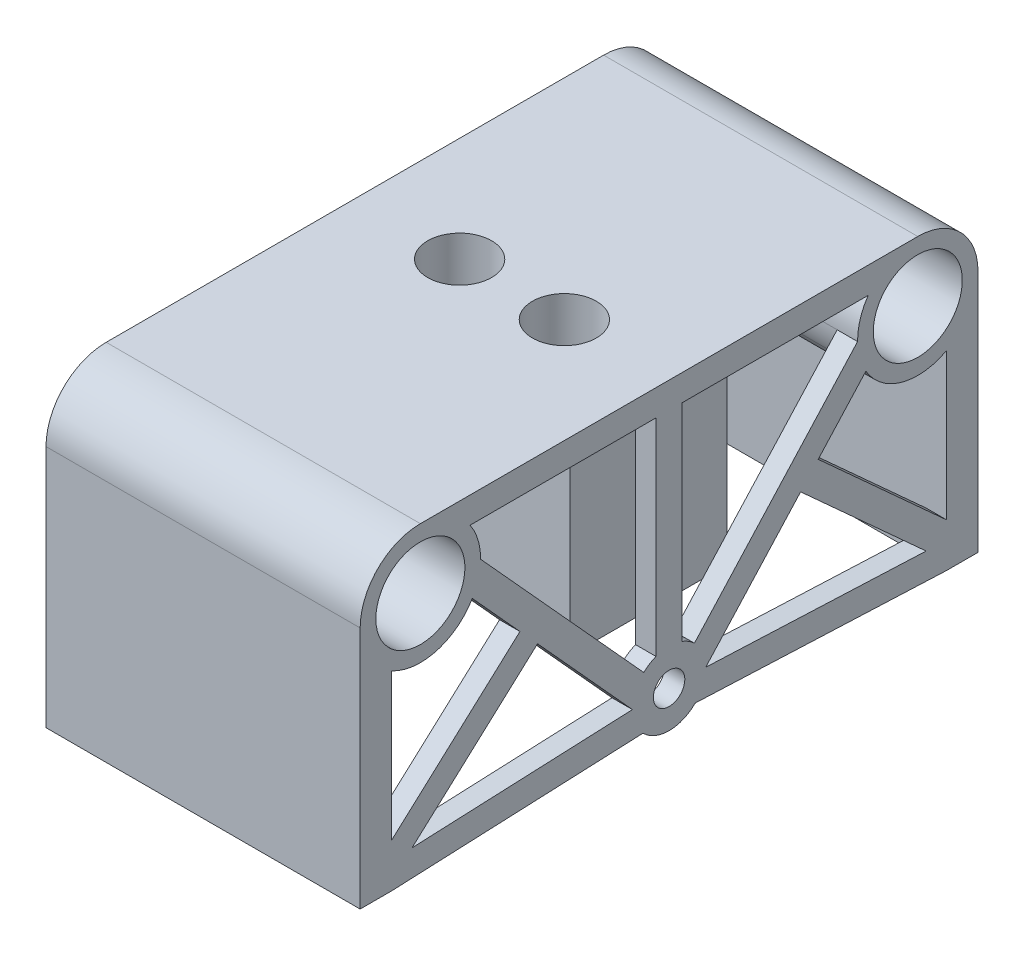
SolidWorks part; units mm, degrees
ref_plane "Front Plane" through (0, 0, 0) normal (0, 0, 1) x (1, 0, 0)
ref_plane "Top Plane" through (0, 0, 0) normal (0, 1, 0) x (1, 0, 0)
ref_plane "Right Plane" through (0, 0, 0) normal (1, 0, 0) x (0, 0, -1)
sketch "Sketch4" plane through (0, 0, 0) normal (0, 0, 1) x (1, 0, 0)
  line L0 (-30, 29) -> (-30, -29)
  line L1 (-30, -29) -> (30, -29)
  line L2 (30, -29) -> (30, 29)
  line L3 (30, 29) -> (-30, 29)
  point P4 (30, 0)
  point P5 (0, 29)
  dimension "D1" = 58
  dimension "D2" = 60
extrude "Boss-Extrude2" add sketch "Sketch4" along normal mid plane 118
sketch "Sketch5" plane through (30, 0, 0) normal (1, 0, 0) x (0, 0, -1)
  line L0 (-7.1278, -22) -> (-53.0521, -25.7381) construction
  line L1 (-53.0521, -30.7546) -> (-5.035, -26.8462) construction
  line L2 (-39.0141, 14.8656) -> (-7.1278, -22) construction
  line L3 (-53.0521, -30.7546) -> (-53.0521, 7.429) construction
  line L6 (-36.121, 19.1639) -> (-4.8602, -16.9785)
  line L8 (-38.0132, 24) -> (-2.4867, 24)
  line L10 (0, -22) -> (0, 29) construction
  line L11 (-2.4867, 24) -> (-2.4867, -15.4691)
  line L29 (0, 0) -> (0, 42.8689) construction
  line L30 (-59, 29) -> (59, 29) construction
  line L31 (-59, -29) -> (-59, 29) construction
  line L32 (-48.8335, -25.3947) -> (-23.2963, -3.3067) construction
  line L33 (-26.5672, 0.475) -> (-53.0521, -22.4327)
  line L34 (-43.6385, -14.2906) -> (-40.3676, -18.0723) construction
  line L35 (-42.0031, -16.1814) -> (-53.0521, -25.7381) construction
  line L36 (-26.5672, 0.475) -> (-37.0815, 12.6313)
  line L37 (-53.0521, 7.429) -> (-53.0521, -22.4327)
  line L38 (-23.2963, -3.3067) -> (-48.8335, -25.3947)
  line L39 (-48.8335, -25.3947) -> (-7.1278, -22)
  line L40 (-7.1278, -22) -> (-23.2963, -3.3067)
  line L41 (-5.035, -26.8462) -> (-53.0521, -30.7546)
  line L42 (-53.0521, -30.7546) -> (53.0521, -30.7546)
  line L43 (5.035, -26.8462) -> (53.0521, -30.7546)
  line L44 (38.0132, 24) -> (2.4867, 24)
  line L45 (2.4867, 24) -> (2.4867, -15.4691)
  line L46 (36.121, 19.1639) -> (4.8602, -16.9785)
  line L47 (48.8335, -25.3947) -> (7.1278, -22)
  line L48 (23.2963, -3.3067) -> (48.8335, -25.3947)
  line L49 (7.1278, -22) -> (23.2963, -3.3067)
  line L50 (26.5672, 0.475) -> (37.0815, 12.6313)
  line L51 (26.5672, 0.475) -> (53.0521, -22.4327)
  line L52 (53.0521, 7.429) -> (53.0521, -22.4327)
  line L53 (-47.5, 17.5) -> (0, 17.5) construction
  line L54 (0, 17.5) -> (0, -22) construction
  circle A8 centre (-47.5, 17.5) radius 8.5
  circle A9 centre (-47.5, 17.5) radius 11.5
  circle A10 centre (47.5, 17.5) radius 8.5
  circle A11 centre (47.5, 17.5) radius 11.5
  circle A12 centre (0, -22) radius 3
  arc A13 (-53.0521, 7.429) -> (-37.0815, 12.6313) centre (-47.5, 17.5) ccw
  arc A14 (-5.035, -26.8462) -> (5.035, -26.8462) centre (0, -22) ccw
  arc A15 (-38.0132, 24) -> (-36.121, 19.1639) centre (-47.5, 17.5) cw
  arc A16 (2.4867, -15.4691) -> (4.8602, -16.9785) centre (0, -22) cw
  arc A17 (-2.4867, -15.4691) -> (-4.8602, -16.9785) centre (0, -22) ccw
  arc A18 (38.0132, 24) -> (36.121, 19.1639) centre (47.5, 17.5) ccw
  arc A19 (53.0521, 7.429) -> (37.0815, 12.6313) centre (47.5, 17.5) cw
  point P3 (-47.5, 17.5)
  point P18 (0, -30.7546)
  point P27 (-42.0031, -16.1814)
  point P58 (59, 17.5)
  dimension "D1" = 17
  dimension "D4" = 6
  dimension "D3" = 5
  dimension "D5" = 39.5
  dimension "D6" = 5
  dimension "D7" = 5
  dimension "D2" = 3
sketch "Sketch6" plane through (-30, 0, 0) normal (-1, 0, 0) x (0, 0, 1)
  line L0 (0, -6.9366) -> (0, 49.2251) construction
  line L1 (0, -22) -> (0, 29) construction
  line L2 (-7, -22) -> (-53, -23.9953) construction
  line L3 (-53, -29) -> (-4.9821, -26.9172) construction
  line L4 (-39.7346, 14.0434) -> (-7, -22) construction
  line L5 (-53, -29) -> (-53, 7.4005) construction
  line L8 (-36.0007, 17.3692) -> (-4.8392, -16.9421)
  line L10 (-38.0132, 24) -> (-2.5, 24)
  line L12 (0, -22) -> (0, 29) construction
  line L13 (-2.5, 24) -> (-2.5, -15.4617)
  line L31 (-49.095, -23.8259) -> (-25.1183, -2.0503) construction
  line L32 (-28.4798, 1.651) -> (-53, -20.6182)
  line L33 (-43.8665, -12.3231) -> (-40.505, -16.0245) construction
  line L34 (-42.1857, -14.1738) -> (-53, -23.9953) construction
  line L35 (-28.4798, 1.651) -> (-37.5841, 11.6756)
  line L36 (-53, 7.4005) -> (-53, -20.6182)
  line L37 (-25.1183, -2.0503) -> (-49.095, -23.8259)
  line L38 (-49.095, -23.8259) -> (-7, -22)
  line L39 (-7, -22) -> (-25.1183, -2.0503)
  line L40 (-4.9821, -26.9172) -> (-53, -29)
  line L42 (4.9821, -26.9172) -> (53, -29)
  line L43 (38.0132, 24) -> (2.5, 24)
  line L44 (2.5, 24) -> (2.5, -15.4617)
  line L45 (36.0007, 17.3692) -> (4.8392, -16.9421)
  line L46 (49.095, -23.8259) -> (7, -22)
  line L47 (25.1182, -2.0503) -> (49.095, -23.8259)
  line L48 (7, -22) -> (25.1182, -2.0503)
  line L49 (28.4798, 1.651) -> (37.584, 11.6756)
  line L50 (28.4798, 1.651) -> (53, -20.6182)
  line L51 (53, 7.4005) -> (53, -20.6182)
  line L52 (-53, -29) -> (-53, -39.7033)
  line L53 (-53, -39.7033) -> (53, -37.9369)
  line L54 (53, -37.9369) -> (53, -29)
  line L55 (-47.5, 29) -> (-47.5, 35.7267)
  line L56 (-47.5, 35.7267) -> (-66.8543, 35.7267)
  line L57 (-66.8543, 35.7267) -> (-66.1473, 17.5)
  line L58 (-66.1473, 17.5) -> (-59, 17.5)
  line L59 (47.5, 29) -> (47.0761, 34.9367)
  line L60 (47.0761, 34.9367) -> (67.1714, 34.5747)
  line L61 (67.1714, 34.5747) -> (67.1714, 17.5)
  line L62 (67.1714, 17.5) -> (59, 17.5)
  circle A0 centre (-47.5, 17.5) radius 8.5
  arc A1 (-47.5, 29) -> (-59, 17.5) centre (-47.5, 17.5) ccw
  circle A10 centre (0, -22) radius 3
  arc A11 (-53, 7.4005) -> (-37.5841, 11.6756) centre (-47.5, 17.5) ccw
  arc A12 (-4.9821, -26.9172) -> (4.9821, -26.9172) centre (0, -22) ccw
  arc A13 (-38.0132, 24) -> (-36.0007, 17.3692) centre (-47.5, 17.5) cw
  arc A14 (2.5, -15.4617) -> (4.8392, -16.9421) centre (0, -22) cw
  arc A15 (-2.5, -15.4617) -> (-4.8392, -16.9421) centre (0, -22) ccw
  arc A16 (38.0132, 24) -> (36.0007, 17.3692) centre (47.5, 17.5) ccw
  arc A17 (53, 7.4005) -> (37.584, 11.6756) centre (47.5, 17.5) cw
  circle A18 centre (47.5, 17.5) radius 8.5
  circle A19 centre (-47.5, 17.5) radius 11.5 construction
  arc A20 (-53, 7.4005) -> (-38.0132, 24) centre (-47.5, 17.5) ccw
  arc A21 (37.0273, 22.251) -> (38.0132, 24) centre (47.5, 17.5) cw
  arc A22 (47.5, 29) -> (59, 17.5) centre (47.5, 17.5) cw
  arc A23 (53, 7.4005) -> (51.5815, 6.7487) centre (47.5, 17.5) cw
  point P13 (-47.5, 17.5)
  point P28 (0, -29)
  point P37 (-42.1857, -14.1738)
  line M23 (-59, 29) -> (-59, -29)
  line M24 (-59, -29) -> (59, -29)
  line M25 (59, -29) -> (59, 29)
  line M26 (59, 29) -> (-59, 29)
  dimension "D2" = 17
  dimension "D1" = 3
extrude "Cut-Extrude2" cut sketch "Sketch6" against normal through all contours L57 L58 L55 L56 M23 M26 | A1 M26 M23 | A0 | A15 L13 L10 A13 L8 | A20 L36 L32 L35 | L38 L39 L37 | A12 L40 M24 | A12 L42 M24 | A10 | A16 L43 L44 A14 L45 | L48 L46 L47 | L51 A17 L49 L50 | A18 | L62 L61 L60 L59 M26 M25 | A22 M26 M25
sketch "Sketch7" plane through (-30, 0, 0) normal (-1, 0, 0) x (0, 0, 1)
  line L9 (-15, 24) -> (-15, -11)
  line L10 (-38.0132, 24) -> (-2.5, 24) construction
  line L11 (-15, -11) -> (15.389, -11)
  line L12 (15.389, -11) -> (15, 24)
  line L14 (15, 24) -> (-15, 24)
  line L15 (47.5, 29) -> (-47.5, 29) construction
  point P5 (0, 24)
  dimension "D1" = 30
  dimension "D2" = 40
extrude "Boss-Extrude3" add sketch "Sketch7" along normal mid plane 52.2 from surface at -30 starting at plane "Right Plane"
sketch "Sketch8" plane through (-26.1, 0, 0) normal (-1, 0, 0) x (0, 0, 1)
  line L0 (-15, 24) -> (-38.0132, 24)
  line L1 (0, 0) -> (0, 26.1631) construction
  line L2 (-15, 24) -> (-15, -11)
  line L3 (-53, 7.4005) -> (-53, -24.0111)
  line L8 (-15, -11) -> (-14.2011, -11)
  line L10 (53, 7.4005) -> (53, -24.0111)
  line L15 (15, 24) -> (15, -11)
  line L16 (15, 24) -> (38.0132, 24)
  line L17 (-14.2011, -11) -> (15, -11)
  line L18 (-53, -24.0111) -> (-53, -39.4582)
  line L19 (-53, -39.4582) -> (53, -37.6121)
  line L20 (53, -37.6121) -> (53, -24.0111)
  arc A1 (-53, 7.4005) -> (-38.0132, 24) centre (-47.5, 17.5) ccw
  arc A7 (38.0132, 24) -> (53, 7.4005) centre (47.5, 17.5) ccw
  point P37 (47.5, 17.5)
extrude "Cut-Extrude7" cut sketch "Sketch8" against normal up to surface (52.2 mm away) contours A7 L10 L20 L19 L18 L3 A1 L0 L2 L8 L17 L15 L16 up to face at (26.1, 4.1211, 9.1125)
sketch "Sketch9" plane through (0, 29, 0) normal (0, 1, 0) x (1, 0, 0)
  line L0 (30, 0) -> (-30, 0) construction
  line L3 (0, 0) -> (0, 34.2384) construction
  circle A0 centre (-10, 0) radius 6.1
  circle A1 centre (10, 0) radius 6.1
  point P4 (0, 0)
  dimension "D1" = 12.2
  dimension "D2" = 10
extrude "Cut-Extrude8" cut sketch "Sketch9" against normal through all
